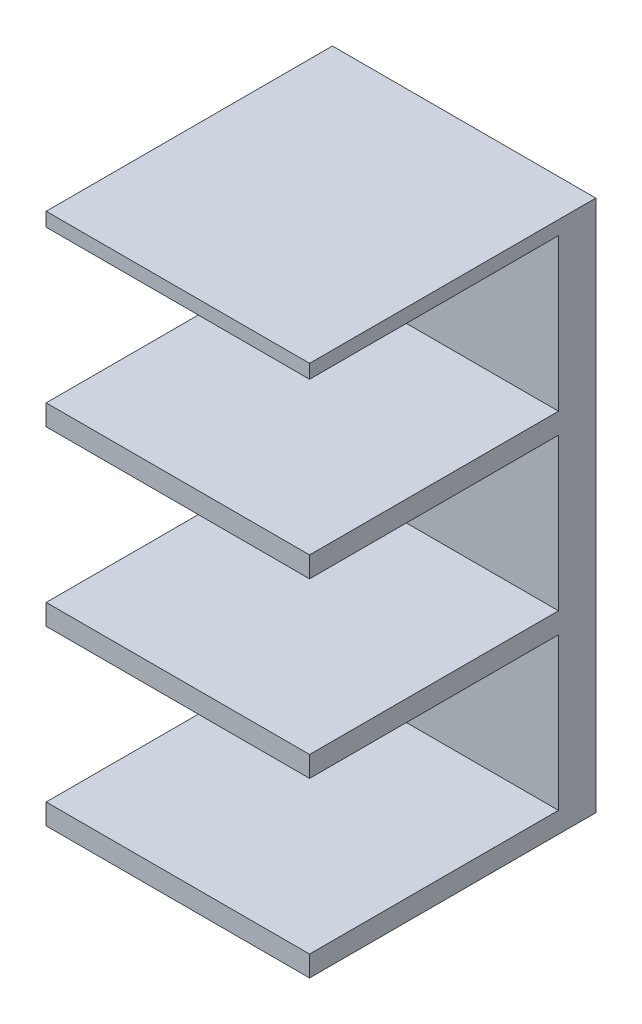
SolidWorks part; units mm, degrees
ref_plane "前视基准面" through (0, 0, 0) normal (0, 0, 1) x (1, 0, 0)
ref_plane "上视基准面" through (0, 0, 0) normal (0, 1, 0) x (1, 0, 0)
ref_plane "右视基准面" through (0, 0, 0) normal (1, 0, 0) x (0, 0, -1)
sketch "草图1" plane through (0, 0, 0) normal (0, 1, 0) x (1, 0, 0)
  line L1 (-875, -900) -> (875, -900)
  line L2 (-875, -900) -> (-875, 900)
  line L3 (-875, 900) -> (875, 900)
  line L4 (875, -900) -> (875, 900)
  line L5 (-875, -900) -> (875, 900) construction
  line L6 (-875, 900) -> (875, -900) construction
  point P0 (0, 0)
extrude "凸台-拉伸3" add sketch "草图1" against normal blind 150
ref_plane "基准面1" through (0, 1250, 0) normal (0, 1, 0) x (1, 0, 0)
ref_plane "基准面2" through (0, 2500, 0) normal (0, 1, 0) x (1, 0, 0)
sketch "草图2" plane through (0, 1250, 0) normal (0, 1, 0) x (1, 0, 0)
  line L1 (-875, -900) -> (875, -900)
  line L2 (-875, -900) -> (-875, 900)
  line L3 (-875, 900) -> (875, 900)
  line L4 (875, -900) -> (875, 900)
  line L5 (-875, -900) -> (875, 900) construction
  line L6 (-875, 900) -> (875, -900) construction
  point P0 (0, 0)
extrude "凸台-拉伸5" add sketch "草图2" against normal blind 150 separate body
sketch "草图3" plane through (0, 2500, 0) normal (0, 1, 0) x (1, 0, 0)
  line L1 (-875, -900) -> (875, -900)
  line L2 (-875, -900) -> (-875, 900)
  line L3 (-875, 900) -> (875, 900)
  line L4 (875, -900) -> (875, 900)
  line L5 (-875, -900) -> (875, 900) construction
  line L6 (-875, 900) -> (875, -900) construction
  point P0 (0, 0)
extrude "凸台-拉伸6" add sketch "草图3" against normal blind 150 separate body
sketch "草图4" plane through (0, 0, 0) normal (0, 1, 0) x (1, 0, 0)
  line L1 (-875, 900) -> (875, 900)
  line L2 (-875, 900) -> (-875, 1170)
  line L3 (-875, 1170) -> (875, 1170)
  line L4 (875, 900) -> (875, 1170)
  dimension "D1" = 270
sketch "草图5" plane through (0, 2500, 0) normal (0, 1, 0) x (1, 0, 0)
  line L1 (-875, 900) -> (875, 900)
  line L2 (-875, 900) -> (-875, 1170)
  line L3 (-875, 1170) -> (875, 1170)
  line L4 (875, 900) -> (875, 1170)
ref_plane "基准面3" through (0, 3600, 0) normal (0, 1, 0) x (1, 0, 0)
sketch "草图7" plane through (0, 3600, 0) normal (0, 1, 0) x (1, 0, 0)
  line L0 (875, -900) -> (875, 900) construction
  line L1 (-875, 900) -> (875, 900)
  line L2 (-875, 900) -> (-875, -900)
  line L3 (-875, -900) -> (875, -900)
  line L4 (875, 900) -> (875, -900)
extrude "凸台-拉伸10" add sketch "草图7" along normal blind 100 separate body
extrude "凸台-拉伸11" add sketch "草图4" along normal mid plane 7400
sketch "草图8" plane through (0, 0, 0) normal (0, 0, 1) x (1, 0, 0)
  line L1 (-875, -150) -> (875, -150)
  line L2 (-875, -150) -> (-875, -3700)
  line L3 (-875, -3700) -> (875, -3700)
  line L4 (875, -150) -> (875, -3700)
extrude "切除-拉伸1" cut sketch "草图8" against normal blind 7400
sketch "草图9" plane through (0, 0, 0) normal (1, 0, 0) x (0, 0, -1)
  line L0 (-900, 3700) -> (1170, 3700)
  line L1 (-900, 3700) -> (1170, 3700) construction
  line L2 (1170, 3700) -> (1170, -150)
  line L3 (1170, -150) -> (-900, -150)
  line L4 (-900, -150) -> (-900, 0)
  line L5 (-900, 0) -> (900, 0)
  line L6 (900, 0) -> (900, 1100)
  line L7 (900, 1100) -> (900, 0) construction
  line L8 (900, 1100) -> (-900, 1100)
  line L9 (-900, 1100) -> (-900, 1250)
  line L10 (962.5, 1250) -> (-962.5, 1250) construction
  line L11 (-900, 1250) -> (900, 1250)
  line L12 (900, 1250) -> (900, 2350)
  line L13 (900, 2350) -> (900, 1250) construction
  line L14 (900, 2350) -> (-900, 2350)
  line L15 (-900, 2350) -> (-900, 2500)
  line L16 (962.5, 2500) -> (-962.5, 2500) construction
  line L17 (-900, 2500) -> (900, 2500)
  line L18 (900, 2500) -> (900, 3600)
  line L19 (962.5, 3600) -> (-962.5, 3600) construction
  line L20 (900, 3600) -> (900, 2500) construction
  line L21 (900, 3600) -> (-900, 3600)
  line L22 (-900, 3600) -> (-900, 3700)
extrude "凸台-拉伸13" add sketch "草图9" along normal blind 1030
